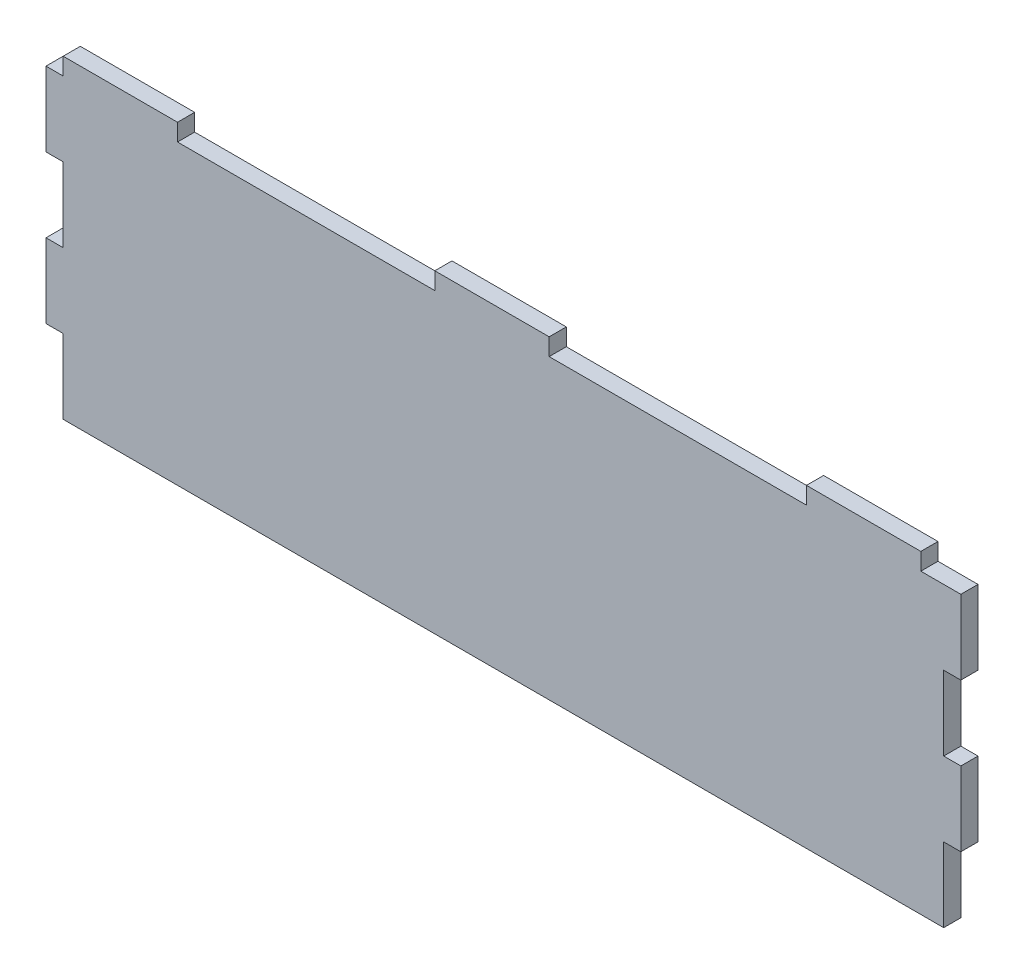
SolidWorks part; units mm, degrees
ref_plane "Front Plane" through (0, 0, 0) normal (0, 0, 1) x (1, 0, 0)
ref_plane "Top Plane" through (0, 0, 0) normal (0, 1, 0) x (1, 0, 0)
ref_plane "Right Plane" through (0, 0, 0) normal (1, 0, 0) x (0, 0, -1)
sketch "Sketch1" plane through (0, 0, 0) normal (0, 0, 1) x (1, 0, 0)
  line L0 (-80, 24.5) -> (-77, 24.5)
  line L1 (-77, 27.5) -> (-57, 27.5)
  line L2 (-80, 24.5) -> (-80, 11.5)
  line L3 (-77, -27.5) -> (77, -27.5)
  line L4 (80, 24.5) -> (80, 11.5)
  line L5 (-77, 26.4687) -> (77, -26.4687) construction
  line L6 (-77, -26.4688) -> (73, 25.0937) construction
  line L7 (-77, 27.5) -> (-77, 24.5)
  line L8 (-57, 27.5) -> (-57, 24.5)
  line L9 (77, 27.5) -> (77, 26.4687)
  line L10 (-12, 27.5) -> (-12, 24.5)
  line L11 (8, 27.5) -> (8, 24.5)
  line L12 (53, 27.5) -> (53, 24.5)
  line L13 (73, 27.5) -> (73, 24.5)
  line L14 (-83.6982, 11.5) -> (86.1301, 11.5) construction
  line L15 (-83.6982, -1.5) -> (86.1301, -1.5) construction
  line L16 (-83.6982, -14.5) -> (86.1301, -14.5) construction
  line L17 (-80, 11.5) -> (-77, 11.5)
  line L18 (-80, -1.5) -> (-77, -1.5)
  line L19 (-80, -14.5) -> (-77, -14.5)
  line L20 (77, 11.5) -> (80, 11.5)
  line L21 (80, -1.5) -> (77, -1.5)
  line L22 (80, -14.5) -> (77, -14.5)
  line L23 (-80, -1.5) -> (-80, -14.5)
  line L24 (-77, 11.5) -> (-77, -1.5)
  line L25 (-77, -14.5) -> (-77, -27.5)
  line L26 (77, 11.5) -> (77, -1.5)
  line L27 (77, -14.5) -> (77, -27.5)
  line L28 (80, -1.5) -> (80, -14.5)
  line L29 (77, 26.4687) -> (80, 27.5) construction
  line L30 (-12, 27.5) -> (8, 27.5)
  line L31 (53, 27.5) -> (73, 27.5)
  line L32 (8, 24.5) -> (53, 24.5)
  line L33 (73, 24.5) -> (80, 24.5)
  line L34 (-57, 24.5) -> (-12, 24.5)
  point P0 (0, 0)
  point P14 (-57, 26)
  dimension "D2" = 3
  dimension "D3" = 55
  dimension "D4" = 3
  dimension "D5" = 3
  dimension "D6" = 20
  dimension "D7" = 20
  dimension "D8" = 45
  dimension "D9" = 45
  dimension "D10" = 20
  dimension "D11" = 13
  dimension "D12" = 3
extrude "Boss-Extrude1" add sketch "Sketch1" along normal blind 3 contours L34 L8 L1 L7 L0 L2 L17 L24 L18 L23 L19 L25 L3 L27 L22 L28 L21 L26 L20 L4 L33 L13 L31 L12 L32 L11 L30 L10
